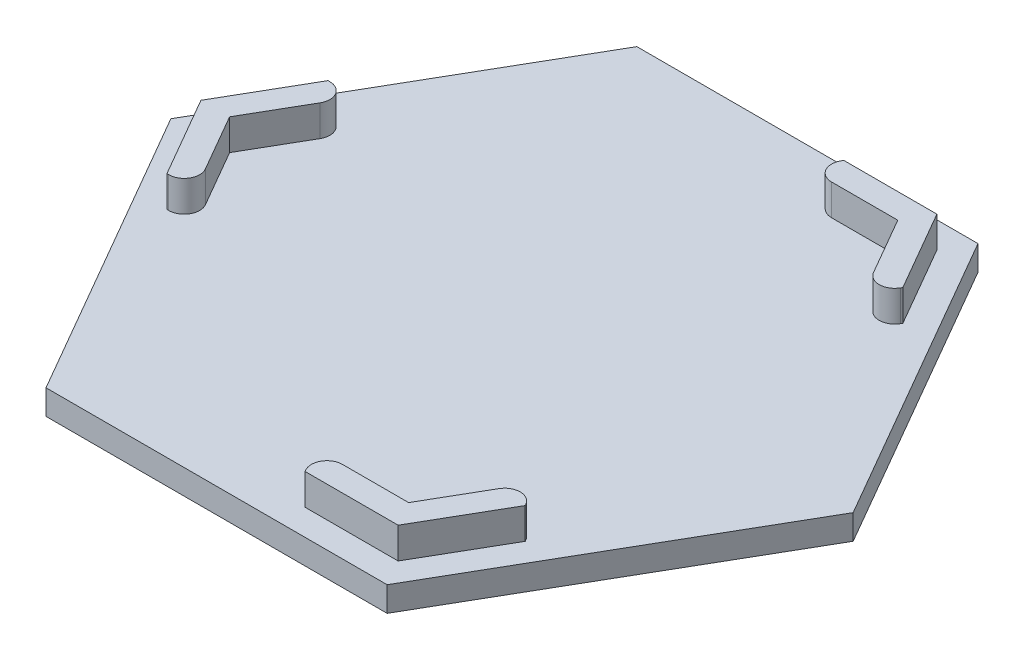
SolidWorks part; units mm, degrees
ref_plane "Front Plane" through (0, 0, 0) normal (0, 0, 1) x (1, 0, 0)
ref_plane "Top Plane" through (0, 0, 0) normal (0, 1, 0) x (1, 0, 0)
ref_plane "Right Plane" through (0, 0, 0) normal (1, 0, 0) x (0, 0, -1)
sketch "Sketch1" plane through (0, 0, 0) normal (0, 1, 0) x (1, 0, 0)
  line L1 (27.94, 0) -> (13.97, 24.1967)
  line L2 (13.97, 24.1967) -> (-13.97, 24.1967)
  line L3 (-13.97, 24.1967) -> (-27.94, 0)
  line L4 (-27.94, 0) -> (-13.97, -24.1967)
  line L5 (-13.97, -24.1967) -> (13.97, -24.1967)
  line L6 (13.97, -24.1967) -> (27.94, 0)
  circle A0 centre (0, 0) radius 24.1967 construction
  dimension "D1" = 55.88
extrude "Boss-Extrude1" add sketch "Sketch1" along normal blind 2.032
sketch "Sketch2" plane through (0, 2.032, 0) normal (0, 1, 0) x (1, 0, 0)
  line L0 (11.565, -20.0311) -> (3.945, -20.0311)
  line L1 (3.945, -20.0311) -> (5.1182, -22.0631)
  line L2 (12.7382, -22.0631) -> (5.1182, -22.0631)
  line L3 (16.5482, -15.464) -> (12.7382, -22.0631)
  line L4 (16.5482, -15.464) -> (15.375, -13.432)
  line L5 (15.375, -13.432) -> (11.565, -20.0311)
  line L6 (-23.13, 0) -> (-19.32, 6.5991)
  line L7 (11.565, -20.0311) -> (23.13, 0) construction
  line L8 (23.13, 0) -> (11.565, 20.0311) construction
  line L9 (11.565, 20.0311) -> (-11.565, 20.0311) construction
  line L10 (-11.565, 20.0311) -> (-23.13, 0) construction
  line L11 (-23.13, 0) -> (-11.565, -20.0311) construction
  line L12 (-11.565, -20.0311) -> (11.565, -20.0311) construction
  line L13 (12.7382, -22.0631) -> (25.4763, 0)
  line L14 (25.4763, 0) -> (12.7382, 22.0631)
  line L15 (12.7382, 22.0631) -> (-12.7382, 22.0631)
  line L16 (-12.7382, 22.0631) -> (-25.4763, 0)
  line L17 (-25.4763, 0) -> (-12.7382, -22.0631)
  line L18 (-12.7382, -22.0631) -> (12.7382, -22.0631)
  line L19 (12.7382, -22.0631) -> (25.4763, 0) construction
  line L20 (25.4763, 0) -> (12.7382, 22.0631) construction
  line L21 (12.7382, 22.0631) -> (-12.7382, 22.0631) construction
  line L22 (-12.7382, 22.0631) -> (-25.4763, 0) construction
  line L23 (-25.4763, 0) -> (-12.7382, -22.0631) construction
  line L24 (-12.7382, -22.0631) -> (12.7382, -22.0631) construction
  line L25 (5.1182, 22.0631) -> (3.945, 20.0311)
  line L26 (15.375, 13.432) -> (16.5482, 15.464)
  line L27 (5.1182, 22.0631) -> (12.7382, 22.0631)
  line L28 (12.7382, 22.0631) -> (16.5482, 15.464)
  line L29 (3.945, 20.0311) -> (11.565, 20.0311)
  line L30 (11.565, 20.0311) -> (15.375, 13.432)
  line L31 (-19.32, 6.5991) -> (-21.6663, 6.5991)
  line L32 (-25.4763, 0) -> (-21.6663, 6.5991)
  line L33 (-21.6663, -6.5991) -> (-25.4763, 0)
  line L34 (-21.6663, -6.5991) -> (-19.32, -6.5991)
  line L35 (-19.32, -6.5991) -> (-23.13, 0)
  line L36 (-13.97, 24.1967) -> (-27.94, 0) construction
  point P16 (-7.854, 10.0376)
  point P17 (0, 0)
  point P18 (2.8231, 17.8314)
  point P31 (0, 0)
  dimension "D4" = 7.62
  dimension "D5" = 3
  dimension "D1" = 2.1336
  dimension "D2" = 2.032
extrude "Boss-Extrude2" add sketch "Sketch2" along normal blind 2.54
fillet "Fillet2" radius 1.27 6 edges at (-19.32, 3.302, -6.5991) (-19.32, 3.302, 6.5991) (3.945, 3.302, 20.0311) (15.375, 3.302, 13.432) (15.375, 3.302, -13.432) (3.945, 3.302, -20.0311)
